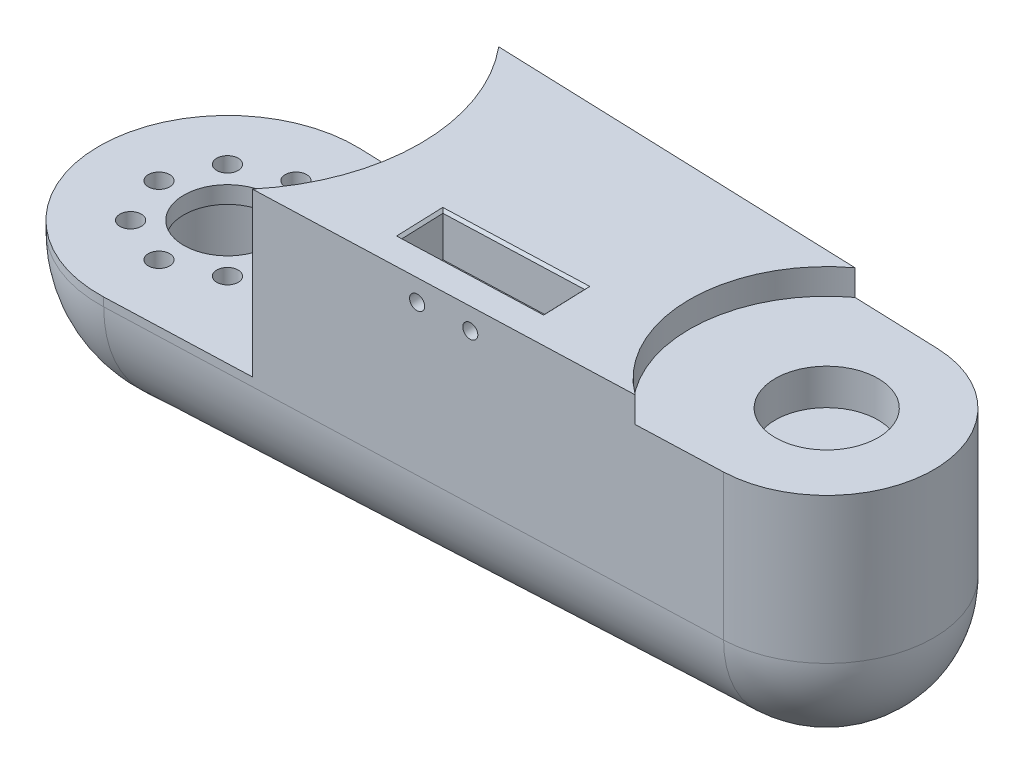
SolidWorks part; units mm, degrees
other "标注1"
sketch "草图20" plane through (82.5, 15, -19.5959) normal (0.2045, 0.9698, -0.1329) x (0.9753, -0.2135, -0.0568)
ref_plane "前视基准面" through (0, 0, 0) normal (0, 0, 1) x (1, 0, 0)
ref_plane "上视基准面" through (0, 0, 0) normal (0, 1, 0) x (1, 0, 0)
ref_plane "右视基准面" through (0, 0, 0) normal (1, 0, 0) x (0, 0, -1)
other "Configuration Table"
sketch "草图1" plane through (0, 0, 0) normal (0, 1, 0) x (1, 0, 0)
  line L2 (0.5357, -14.9904) -> (70.4464, -12.492)
  line L4 (-15, 0) -> (82.5, 0)
  arc A1 (70.4464, -12.492) -> (82.5, 0) centre (70, 0) ccw
  arc A3 (-15, 0) -> (0.5357, -14.9904) centre (0, 0) ccw
  dimension "D1" = 15
  dimension "D2" = 70
  dimension "D3" = 25
ref_axis "基准轴1" through (70, 0, 0) along (-1, 0, 0)
sketch "草图2" plane through (0, 0, 0) normal (0, 1, 0) x (1, 0, 0)
  line L0 (0.5357, 14.9904) -> (70.4464, 12.492)
  line L2 (0.5357, -14.9904) -> (70.4464, -12.492)
  line L3 (82.5, 0) -> (-15, 0)
  line L4 (0.5357, -14.9904) -> (70.4464, -12.492)
  line L5 (82.5, 0) -> (-15, 0)
  arc A2 (70.4464, -12.492) -> (82.5, 0) centre (70, 0) ccw
  arc A3 (-15, 0) -> (0.5357, -14.9904) centre (0, 0) ccw
  arc A4 (70.4464, -12.492) -> (70.4464, 12.492) centre (70, 0) ccw
  arc A5 (0.5357, 14.9904) -> (0.5357, -14.9904) centre (0, 0) ccw
  dimension "D1" = 0
extrude "凸台-拉伸1" add sketch "草图2" along normal blind 20 contours L0 A5 L5 A4 | L5 A5 L4 A4
revolve "旋转1" add sketch "草图1" angle 180 about axis through (70, 0, 0) along (-1, 0, 0)
sketch "草图3" plane through (0, 20, 0) normal (0, 1, 0) x (1, 0, 0)
  line L2 (70.4464, 12.492) -> (0.5357, 14.9904)
  line L3 (0.5357, -14.9904) -> (70.4464, -12.492)
  line L4 (17.2955, 14.3915) -> (0.5357, 14.9904)
  line L5 (0.5357, -14.9904) -> (17.2955, -14.3915)
  arc A0 (17.2955, -14.3915) -> (17.2955, 14.3915) centre (0, 0) ccw
  arc A3 (0.5357, 14.9904) -> (0.5357, -14.9904) centre (0, 0) ccw
  arc A4 (70.4464, -12.492) -> (70.4464, 12.492) centre (70, 0) ccw
  arc A5 (0.5357, 14.9904) -> (0.5357, -14.9904) centre (0, 0) ccw
  dimension "D1" = 45
  dimension "D2" = 0
extrude "切除-拉伸1" cut sketch "草图3" against normal blind 19
sketch "草图4" plane through (0, 1, 0) normal (0, 1, 0) x (1, 0, 0)
  circle A0 centre (0, 0) radius 10
  circle A1 centre (8, 0) radius 1.25
  circle A2 centre (5.6569, -5.6569) radius 1.25
  circle A3 centre (0, -8) radius 1.25
  circle A4 centre (-5.6569, -5.6569) radius 1.25
  circle A5 centre (-8, 0) radius 1.25
  circle A6 centre (-5.6569, 5.6569) radius 1.25
  circle A7 centre (0, 8) radius 1.25
  circle A8 centre (5.6569, 5.6569) radius 1.25
  circle A9 centre (0, 0) radius 5.1
  point P22 (0, 0)
  dimension "D1" = 20
  dimension "D3" = 2.5
  dimension "D5" = 10.2
  dimension "D2" = 8
  dimension "D4" = 8
ref_plane "基准面1" through (0, -1, 0) normal (0, 1, 0) x (1, 0, 0)
sketch "草图5" plane through (0, -1, 0) normal (0, 1, 0) x (1, 0, 0)
  circle A0 centre (0, 0) radius 10 construction
  circle A1 centre (0, 0) radius 10
extrude "切除-拉伸2" cut sketch "草图5" against normal through all
extrude "切除-拉伸3" cut sketch "草图4" against normal through all contours A1 | A2 | A3 | A4 | A5 | A8 | A6 | A7 | A9
sketch "草图11" plane through (0, 20, 0) normal (0, 1, 0) x (1, 0, 0)
  line L0 (70, 0) -> (93.8641, 0) construction
  line L1 (17.2955, 14.3915) -> (70.4464, 12.492) construction
  line L2 (17.2955, -14.3915) -> (70.4464, -12.492) construction
  line L3 (60.4653, 12.8487) -> (70.4464, 12.492)
  line L4 (70.4464, -12.492) -> (60.4653, -12.8487)
  arc A0 (70.4464, -12.492) -> (70.4464, 12.492) centre (70, 0) ccw construction
  arc A1 (70.4464, -12.492) -> (70.4464, 12.492) centre (70, 0) ccw
  arc A2 (60.4653, 12.8487) -> (60.4653, -12.8487) centre (70, 0) ccw
  dimension "D1" = 16
extrude "切除-拉伸5" cut sketch "草图11" against normal blind 3
sketch "草图6" plane through (0, 17, 0) normal (0, 1, 0) x (1, 0, 0)
  arc A0 (70.4464, 12.492) -> (70.4464, -12.492) centre (70, 0) ccw construction
  arc A1 (70.4464, 12.492) -> (70.4464, -12.492) centre (70, 0) ccw
  circle A2 centre (70, 0) radius 3
  circle A3 centre (70, 0) radius 6
  dimension "D1" = 6
  dimension "D2" = 12
extrude "切除-拉伸4" cut sketch "草图6" against normal blind 4.2 contours A3 A2
sketch "草图12" plane through (0, 20, 0) normal (0, 1, 0) x (1, 0, 0)
  line L1 (30.7605, -10.408) -> (46.7503, -9.8366)
  line L3 (46.7503, -9.8366) -> (46.5717, -4.8398)
  line L4 (60.4653, 12.8487) -> (17.2955, 14.3915)
  line L5 (17.2955, -14.3915) -> (60.4653, -12.8487)
  line L7 (17.2955, -14.3915) -> (60.4653, -12.8487)
  line L8 (46.5717, -4.8398) -> (30.5819, -5.4112)
  line L9 (30.5819, -5.4112) -> (30.7605, -10.408)
  line L10 (38.8804, -13.6201) -> (38.3703, 0.6528) construction
  arc A4 (60.4653, 12.8487) -> (60.4653, -12.8487) centre (70, 0) ccw
  arc A5 (17.2955, -14.3915) -> (17.2955, 14.3915) centre (0, 0) ccw
  dimension "D5" = 8
  dimension "D1" = 0
  dimension "D4" = 8
  dimension "D2" = 3.5
  dimension "D3" = 5
extrude "切除-拉伸6" cut sketch "草图12" against normal blind 5 contours L1 L10 L8 L9 | L10 L1 L3 L8
sketch "草图17" plane through (0.5357, 0, 14.9904) normal (0.0357, 0, 0.9994) x (0.9994, 0, -0.0357)
  line L4 (46.3692, 20) -> (30.3692, 20)
  line L5 (46.3692, 15) -> (46.3692, 20)
  line L6 (30.3692, 15) -> (46.3692, 15)
  line L7 (30.3692, 20) -> (30.3692, 15)
  line L8 (46.3692, 20) -> (30.3692, 20)
  line L9 (46.3692, 15) -> (46.3692, 20)
  line L10 (30.3692, 15) -> (46.3692, 15)
  line L11 (30.3692, 20) -> (30.3692, 15)
  point P4 (35.3692, 17.5)
  point P6 (41.3692, 17.5)
  point P9 (30.3692, 17.5)
  dimension "D2" = 5
  dimension "D3" = 5
  dimension "D1" = 0
hole_wizard "孔1" positions "草图18" profile "草图19" legacy
sketch "草图18" plane through (0.5357, 0, 14.9904) normal (0.0357, 0, 0.9994) x (0.9994, 0, -0.0357)
  point P0 (35.3692, 17.5)
  point P3 (41.3692, 17.5)
sketch "草图19" plane through (35.8823, 17.5, 13.7272) normal (0, 1, 0) x (0.9994, 0, -0.0357)
  line L0 (0, 0) -> (0, 3.5)
  line L1 (0, 3.5) -> (0.85, 3.5)
  line L2 (0.85, 3.5) -> (0.85, 0)
  line L3 (0.85, 0) -> (0, 0)
  line L4 (0, 110) -> (0, -10) construction
  dimension "直径" = 1.7
  dimension "深度" = 3.5
chamfer "倒角1" distance 0.3 angle 45 4 edges at (46.661, 20, 7.3382) (38.7554, 20, 10.1223) (30.6712, 20, 7.9096) (38.5768, 20, 5.1255)
